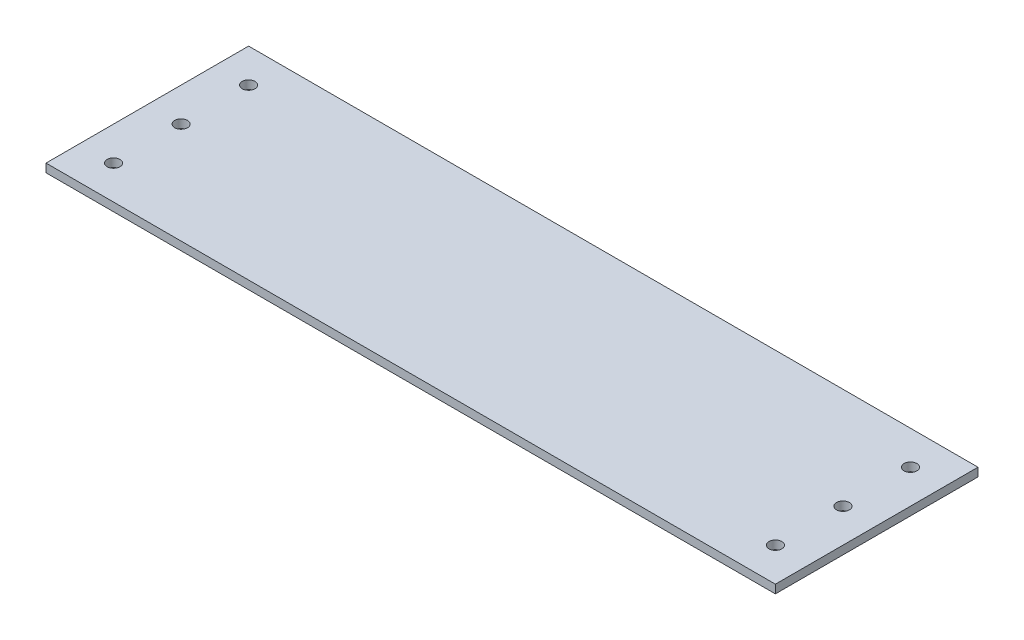
SolidWorks part; units mm, degrees
material "6061 Alloy"
ref_plane "Front Plane" through (0, 0, 0) normal (0, 0, 1) x (1, 0, 0)
ref_plane "Top Plane" through (0, 0, 0) normal (0, 1, 0) x (1, 0, 0)
ref_plane "Right Plane" through (0, 0, 0) normal (1, 0, 0) x (0, 0, -1)
sketch "Sketch1" plane through (0, 0, 0) normal (0, 1, 0) x (1, 0, 0)
  line L0 (0, 38.1) -> (274.32, 38.1) construction
  line L1 (0, 0) -> (274.32, 0)
  line L2 (0, 0) -> (0, 76.2)
  line L3 (0, 76.2) -> (274.32, 76.2)
  line L4 (274.32, 0) -> (274.32, 76.2)
  line L5 (0, 63.5) -> (12.7, 63.5) construction
  line L6 (12.7, 63.5) -> (12.7, 12.7) construction
  line L7 (137.16, 76.2) -> (137.16, 0) construction
  line L8 (12.7, 63.5) -> (261.62, 63.5) construction
  circle A0 centre (12.7, 63.5) radius 2.413
  circle A1 centre (12.7, 38.1) radius 2.413
  circle A2 centre (12.7, 12.7) radius 2.413
  circle A3 centre (261.62, 12.7) radius 2.413
  circle A4 centre (261.62, 38.1) radius 2.413
  circle A5 centre (261.62, 63.5) radius 2.413
  dimension "D3" = 4.826
  dimension "D6" = 12.7
  dimension "D1" = 248.92
  dimension "D2" = 76.2
  dimension "D5" = 12.7
  dimension "D4" = 3
extrude "Boss-Extrude1" add sketch "Sketch1" along normal blind 3.175
